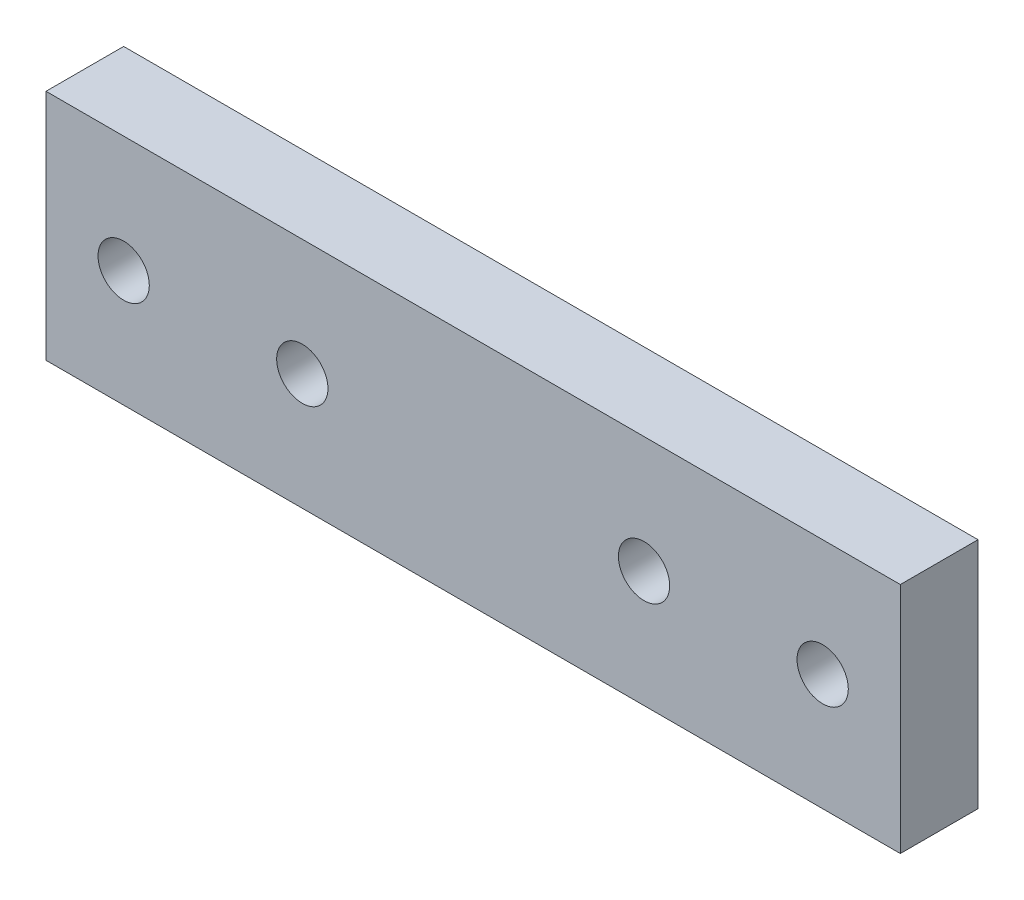
SolidWorks part; units mm, degrees
ref_plane "Front Plane" through (0, 0, 0) normal (0, 0, 1) x (1, 0, 0)
ref_plane "Top Plane" through (0, 0, 0) normal (0, 1, 0) x (1, 0, 0)
ref_plane "Right Plane" through (0, 0, 0) normal (1, 0, 0) x (0, 0, -1)
sketch "Sketch1" plane through (0, 0, 0) normal (0, 0, 1) x (1, 0, 0)
  line L0 (40.8734, 704.4863) -> (-69.1266, 704.4863)
  line L1 (-69.1266, 704.4863) -> (-69.1266, 674.4863)
  line L2 (-69.1266, 674.4863) -> (40.8734, 674.4863)
  line L3 (40.8734, 674.4863) -> (40.8734, 704.4863)
  line L4 (30.8734, 184.0718) -> (30.8734, 674.4863) construction
  line L5 (30.8734, 674.4863) -> (30.8734, 689.4863) construction
  line L6 (30.8734, 689.4863) -> (30.8734, 704.4863) construction
  line L7 (7.8734, 184.0718) -> (7.8734, 674.4863) construction
  line L8 (7.8734, 674.4863) -> (7.8734, 689.4863) construction
  line L9 (-14.1266, 184.0718) -> (-14.1266, 674.4863) construction
  line L10 (-14.1266, 674.4863) -> (-14.1266, 704.4863) construction
  point P16 (-59.1266, 689.4863)
  point P18 (-36.1266, 689.4863)
extrude "Boss-Extrude1" add sketch "Sketch1" along normal blind 10 contours L2 L3 L0 L1
hole_wizard "M6 Clearance Hole" positions "Sketch4" profile "Sketch5" hole size "M6" standard "ISO" end condition through all
sketch "Sketch4" plane through (545.7192, 1586.9579, 10) normal (0, 0, 1) x (-1, 0, 0)
  point P0 (514.8458, 1450.8861)
  point P3 (514.8458, 1412.8861)
  point P6 (537.8458, 1453.8861)
  point P9 (537.8458, 1409.8861)
  point P12 (581.8458, 1453.8861)
  point P15 (581.8458, 1409.8861)
  point P18 (604.8458, 1450.8861)
  point P21 (604.8458, 1412.8861)
  point P24 (514.8458, 897.4716)
  point P27 (537.8458, 897.4716)
  point P30 (581.8458, 897.4716)
  point P33 (604.8458, 897.4716)
  point P36 (394.7524, 1482.1561)
  point P40 (514.8458, 1431.8861)
  point P43 (537.8458, 1431.8861)
  point P47 (581.8458, 1431.8861)
  point P53 (604.8458, 1431.8861)
sketch "Sketch5" plane through (30.8734, 136.0718, 10) normal (1, 0, 0) x (0, -1, 0)
  line L0 (0, 0) -> (0, 10)
  line L1 (0, 10) -> (3.3, 10)
  line L2 (3.3, 10) -> (3.3, 0)
  line L3 (3.3, 0) -> (0, 0)
  line L4 (0, -6.35) -> (0, 107.95) construction
  dimension "Thru Hole Dia." = 6.6
  dimension "Thru Hole Depth" = 10
